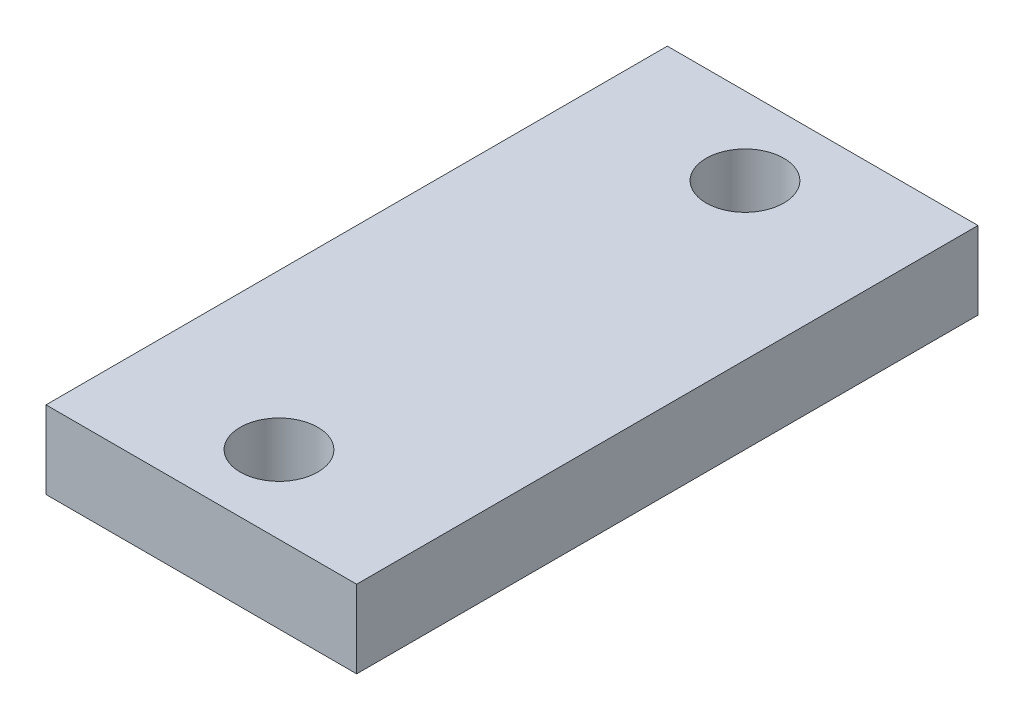
SolidWorks part; units mm, degrees
ref_plane "Front Plane" through (0, 0, 0) normal (0, 0, 1) x (1, 0, 0)
ref_plane "Top Plane" through (0, 0, 0) normal (0, 1, 0) x (1, 0, 0)
ref_plane "Right Plane" through (0, 0, 0) normal (1, 0, 0) x (0, 0, -1)
sketch "Sketch2" plane through (0, 0, 0) normal (0, 1, 0) x (1, 0, 0)
  line L0 (0, 0) -> (12.7, 0)
  line L1 (12.7, 0) -> (12.7, 25.4)
  line L2 (0, 25.4) -> (0, 19.05)
  line L3 (-12.7, -25.4) -> (12.7, -25.4)
  line L4 (-12.7, -25.4) -> (-12.7, 25.4)
  line L5 (-12.7, 25.4) -> (12.7, 25.4)
  line L6 (12.7, -25.4) -> (12.7, 25.4)
  line L7 (0, 25.4) -> (0, -25.4) construction
  line L8 (-12.7, 0) -> (12.7, 0) construction
  line L9 (0, -25.4) -> (0, -19.05)
  circle A0 centre (0, 19.05) radius 3.175
  circle A1 centre (0, -19.05) radius 3.175
extrude "Boss-Extrude1" add sketch "Sketch2" along normal blind 6.35
